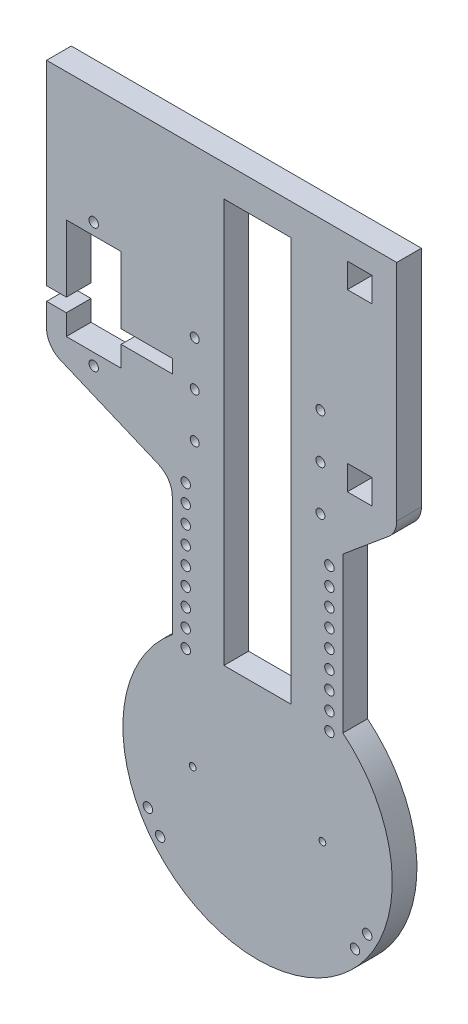
SolidWorks part; units mm, degrees
material "ﾁｰｸ材"
ref_plane "正面" through (0, 0, 0) normal (0, 0, 1) x (1, 0, 0)
ref_plane "平面" through (0, 0, 0) normal (0, 1, 0) x (1, 0, 0)
ref_plane "右側面" through (0, 0, 0) normal (1, 0, 0) x (0, 0, -1)
sketch "ｽｹｯﾁ1" plane through (0, 0, 0) normal (0, 0, 1) x (1, 0, 0)
  line L0 (31, 120) -> (-47, 120)
  line L1 (-19, 53.2164) -> (-19, 23.2164)
  line L4 (-47, 120) -> (-47, 65)
  line L6 (-47, 65) -> (-19, 53.2164)
  line L7 (19, 57.75) -> (31, 67.75)
  line L8 (31, 67.75) -> (31, 120)
  line L10 (19, 57.75) -> (19, 23.2164)
  arc A0 (-19, 23.2164) -> (19, 23.2164) centre (0, 0) ccw
  point P10 (0, 0)
  point P12 (19, 117.807)
  point P13 (34, 125)
  point P14 (34, 112.25)
  point P15 (34, 123.9172)
  dimension "D1" = 60
  dimension "D2" = 120
  dimension "D3" = 19
  dimension "D4" = 47
  dimension "D5" = 55
  dimension "D6" = 30
  dimension "D7" = 67.75
  dimension "D9" = 12
  dimension "D10" = 10
extrude "ﾎﾞｽ - 押し出し1" add sketch "ｽｹｯﾁ1" along normal blind 5.5
sketch "ｽｹｯﾁ3" plane through (0, 0, 5.5) normal (0, 0, 1) x (1, 0, 0)
  line L0 (0, 0) -> (0, 22.4882) construction
sketch "ｽｹｯﾁ4" plane through (0, 0, 5.5) normal (0, 0, 1) x (1, 0, 0)
  line L5 (0, 0) -> (0, 22.4882) construction
  line L6 (0, 0) -> (0, -7.023) construction
  line L12 (25.5, 109.25) -> (20, 109.25)
  line L13 (25.5, 70.25) -> (20, 70.25)
  line L14 (25.5, 70.25) -> (25.5, 75.75)
  line L19 (25.5, 75.75) -> (20, 75.75)
  line L20 (20, 70.25) -> (20, 75.75)
  line L21 (25.5, 70.25) -> (20, 75.75) construction
  line L22 (25.5, 75.75) -> (20, 70.25) construction
  line L23 (25.5, 109.25) -> (25.5, 114.75)
  line L24 (25.5, 114.75) -> (20, 114.75)
  line L25 (20, 109.25) -> (20, 114.75)
  line L26 (25.5, 109.25) -> (20, 114.75) construction
  line L27 (25.5, 114.75) -> (20, 109.25) construction
  circle A0 centre (14, 63) radius 1
  circle A1 centre (14, 83) radius 1
  circle A2 centre (14, 73) radius 1
  circle A3 centre (-14, 83) radius 1
  circle A4 centre (-14, 73) radius 1
  circle A5 centre (-14, 63) radius 1
  point P16 (22.75, 73)
  point P23 (23, 69.4645)
  point P24 (22.75, 112)
  point P29 (22.75, 109.9428)
  dimension "D11" = 5.5
  dimension "D1" = 2
  dimension "D5" = 73
  dimension "D2" = 14
  dimension "D3" = 63
  dimension "D4" = 83
  dimension "D6" = 5.5
  dimension "D7" = 5.5
  dimension "D8" = 20
  dimension "D9" = 39
  dimension "D10" = 5.5
extrude "ｶｯﾄ - 押し出し2" cut sketch "ｽｹｯﾁ4" against normal through all
fillet "ﾌｨﾚｯﾄ1" radius 5 1 edges at (-47, 65, 2.75)
fillet "ﾌｨﾚｯﾄ2" radius 5 1 edges at (-19, 53.2164, 2.75)
sketch "ｽｹｯﾁ5" plane through (0, 0, 5.5) normal (0, 0, 1) x (1, 0, 0)
  circle A0 centre (14.45, 0) radius 0.75
  circle A1 centre (-14.45, 0) radius 0.75
  dimension "D1" = 14.45
  dimension "D2" = 1.5
  dimension "D3" = 14.45
extrude "ｶｯﾄ - 押し出し3" cut sketch "ｽｹｯﾁ5" against normal through all
sketch "ｽｹｯﾁ6" plane through (0, 0, 5.5) normal (0, 0, 1) x (1, 0, 0)
  line L0 (0, 0) -> (-25.1601, -16.3392) construction
  line L1 (0, 0) -> (0, 22.4882) construction
  line L2 (-21.7018, -17.0742) -> (-24.425, -12.8809) construction
  line L3 (0, 0) -> (0, -5.9449) construction
  arc A0 (-19, 23.2164) -> (19, 23.2164) centre (0, 0) ccw construction
  circle A1 centre (-24.425, -12.8809) radius 1.05
  circle A2 centre (-21.7018, -17.0742) radius 1.05
  circle A3 centre (24.425, -12.8809) radius 1.05
  circle A4 centre (21.7018, -17.0742) radius 1.05
  point P12 (-23.0634, -14.9776)
  dimension "D2" = 5
  dimension "D3" = 2.1
  dimension "D4" = 2.1
  dimension "D1" = 123
  dimension "D5" = 27.5
extrude "ｶｯﾄ - 押し出し4" cut sketch "ｽｹｯﾁ6" against normal through all
sketch "ｽｹｯﾁ7" plane through (0, 0, 5.5) normal (0, 0, 1) x (1, 0, 0)
  line L1 (7.5, 23) -> (-7.5, 23)
  line L2 (7.5, 23) -> (7.5, 113)
  line L3 (7.5, 113) -> (-7.5, 113)
  line L4 (-7.5, 23) -> (-7.5, 113)
  line L5 (7.5, 23) -> (-7.5, 113) construction
  line L6 (7.5, 113) -> (-7.5, 23) construction
  point P0 (0, 68)
  dimension "D1" = 15
  dimension "D2" = 90
  dimension "20" = 23
extrude "ｶｯﾄ - 押し出し5" cut sketch "ｽｹｯﾁ7" against normal through all
sketch "ｽｹｯﾁ8" plane through (0, 0, 5.5) normal (0, 0, 1) x (1, 0, 0)
  line L0 (0, 0) -> (0, 22.4882) construction
  line L1 (-19, 73.5) -> (-48.9911, 73.5)
  line L2 (-19, 73.5) -> (-19, 76.5)
  line L3 (-19, 76.5) -> (-48.9911, 76.5)
  line L4 (-48.9911, 73.5) -> (-48.9911, 76.5)
  line L5 (-19, 73.5) -> (-48.9911, 76.5) construction
  line L6 (-19, 76.5) -> (-48.9911, 73.5) construction
  point P0 (-33.9956, 75)
  dimension "D1" = 75
  dimension "D2" = 3
  dimension "D3" = 19
extrude "ｶｯﾄ - 押し出し6" cut sketch "ｽｹｯﾁ8" against normal through all
sketch "ｽｹｯﾁ9" plane through (0, 0, 5.5) normal (0, 0, 1) x (1, 0, 0)
  line L0 (-19, 73.5) -> (-19, 76.5) construction
  line L1 (-30.4, 68.9) -> (-42.6, 68.9)
  line L2 (-30.4, 68.9) -> (-30.4, 91.4)
  line L3 (-30.4, 91.4) -> (-42.6, 91.4)
  line L4 (-42.6, 68.9) -> (-42.6, 91.4)
  line L5 (-30.4, 68.9) -> (-42.6, 91.4) construction
  line L6 (-30.4, 91.4) -> (-42.6, 68.9) construction
  line L7 (0, 0) -> (0, 22.4882) construction
  circle A0 centre (-36.5, 66.3) radius 1.05
  circle A1 centre (-36.5, 94) radius 1.05
  point P0 (-36.5, 80.15)
  point P7 (-19, 75)
  dimension "D4" = 2.6
  dimension "D5" = 2.1
  dimension "D6" = 2.6
  dimension "D1" = 22.5
  dimension "D2" = 12.2
  dimension "D3" = 6.1
  dimension "D7" = 36.5
extrude "ｶｯﾄ - 押し出し7" cut sketch "ｽｹｯﾁ9" against normal through all
fillet "ﾌｨﾚｯﾄ3" radius 5 1 edges at (31, 67.75, 2.75)
sketch "ｽｹｯﾁ10" plane through (0, 0, 5.5) normal (0, 0, 1) x (1, 0, 0)
  line L0 (0, 0) -> (0, 22.4882) construction
  line L1 (0, 0) -> (0, 20.1378) construction
  circle A0 centre (16, 22) radius 1.05
  circle A3 centre (16, 26) radius 1.05
  circle A4 centre (16, 30) radius 1.05
  circle A5 centre (16, 34) radius 1.05
  circle A6 centre (16, 38) radius 1.05
  circle A7 centre (16, 42) radius 1.05
  circle A8 centre (16, 46) radius 1.05
  circle A9 centre (16, 50) radius 1.05
  circle A10 centre (-16, 50) radius 1.05
  circle A11 centre (-16, 46) radius 1.05
  circle A12 centre (-16, 42) radius 1.05
  circle A13 centre (-16, 38) radius 1.05
  circle A14 centre (-16, 34) radius 1.05
  circle A15 centre (-16, 30) radius 1.05
  circle A16 centre (-16, 26) radius 1.05
  circle A17 centre (-16, 22) radius 1.05
  circle A18 centre (16, 54) radius 1.05
  circle A19 centre (-16, 54) radius 1.05
  dimension "D1" = 2.1
  dimension "D2" = 16
  dimension "D3" = 22
  dimension "D4" = 9
extrude "ｶｯﾄ - 押し出し8" cut sketch "ｽｹｯﾁ10" against normal through all
